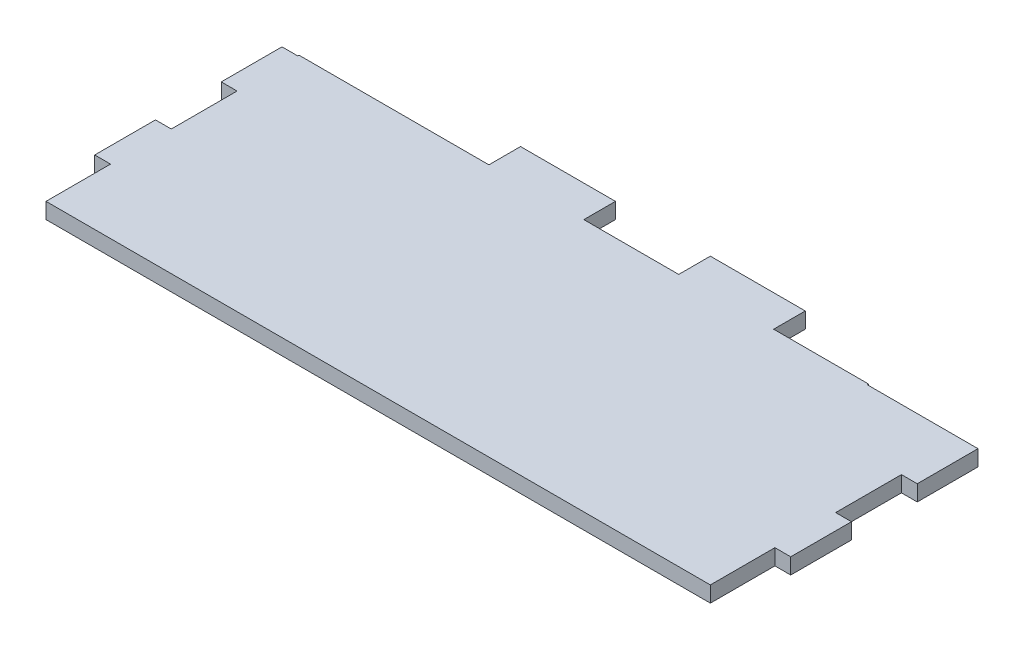
SolidWorks part; units mm, degrees
ref_plane "Front Plane" through (0, 0, 0) normal (0, 0, 1) x (1, 0, 0)
ref_plane "Top Plane" through (0, 0, 0) normal (0, 1, 0) x (1, 0, 0)
ref_plane "Right Plane" through (0, 0, 0) normal (1, 0, 0) x (0, 0, -1)
sketch "Sketch1" plane through (0, 0, 0) normal (0, 1, 0) x (1, 0, 0)
  line L1 (-66.675, -50.8) -> (66.675, -50.8)
  line L2 (-66.675, -50.8) -> (-66.675, 50.8)
  line L3 (-66.675, 50.8) -> (66.675, 50.8)
  line L4 (66.675, -50.8) -> (66.675, 50.8)
  line L5 (-66.675, -50.8) -> (66.675, 50.8) construction
  line L6 (-66.675, 50.8) -> (66.675, -50.8) construction
  point P0 (0, 0)
  dimension "D1" = 133.35
  dimension "D2" = 101.6
extrude "Boss-Extrude1" add sketch "Sketch1" along normal blind 3.175
sketch "Sketch2" plane through (0, 0, 0) normal (0, -1, 0) x (-1, 0, 0)
  line L0 (66.675, 50.8) -> (66.675, -50.8) construction
  line L1 (66.675, -37.846) -> (69.85, -37.846)
  line L2 (66.675, -37.846) -> (66.675, -25.654)
  line L3 (66.675, -25.654) -> (69.85, -25.654)
  line L4 (69.85, -37.846) -> (69.85, -25.654)
  line L6 (66.675, -12.446) -> (69.85, -12.446)
  line L7 (66.675, -12.446) -> (66.675, -0.254)
  line L8 (66.675, -0.254) -> (69.85, -0.254)
  line L9 (69.85, -12.446) -> (69.85, -0.254)
  line L10 (66.675, 12.954) -> (69.85, 12.954)
  line L11 (66.675, 12.954) -> (66.675, 25.146)
  line L12 (66.675, 25.146) -> (69.85, 25.146)
  line L13 (69.85, 12.954) -> (69.85, 25.146)
  line L14 (66.675, 38.354) -> (69.85, 38.354)
  line L15 (66.675, 38.354) -> (66.675, 50.546)
  line L16 (66.675, 50.546) -> (69.85, 50.546)
  line L17 (69.85, 38.354) -> (69.85, 50.546)
  line L18 (0, 0) -> (0, -50.8) construction
  line L19 (66.675, -50.8) -> (-66.675, -50.8) construction
  line L20 (-69.85, 38.354) -> (-69.85, 50.546)
  line L21 (-66.675, 50.546) -> (-69.85, 50.546)
  line L22 (-66.675, 38.354) -> (-66.675, 50.546)
  line L23 (-66.675, 38.354) -> (-69.85, 38.354)
  line L24 (-69.85, 12.954) -> (-69.85, 25.146)
  line L25 (-66.675, 25.146) -> (-69.85, 25.146)
  line L26 (-66.675, 12.954) -> (-66.675, 25.146)
  line L27 (-66.675, 12.954) -> (-69.85, 12.954)
  line L28 (-69.85, -12.446) -> (-69.85, -0.254)
  line L29 (-66.675, -0.254) -> (-69.85, -0.254)
  line L30 (-66.675, -12.446) -> (-66.675, -0.254)
  line L31 (-66.675, -12.446) -> (-69.85, -12.446)
  line L32 (-69.85, -37.846) -> (-69.85, -25.654)
  line L33 (-66.675, -25.654) -> (-69.85, -25.654)
  line L34 (-66.675, -37.846) -> (-66.675, -25.654)
  line L35 (-66.675, -37.846) -> (-69.85, -37.846)
  line L36 (28.575, 57.15) -> (9.525, 57.15)
  line L37 (66.675, 50.8) -> (47.625, 50.8)
  line L38 (66.675, 50.8) -> (66.675, 57.15)
  line L39 (66.675, 57.15) -> (47.625, 57.15)
  line L40 (47.625, 50.8) -> (47.625, 57.15)
  line L41 (9.525, 50.8) -> (9.525, 57.15)
  line L42 (28.575, 50.8) -> (9.525, 50.8)
  line L43 (28.575, 50.8) -> (28.575, 57.15)
  line L44 (-9.525, 57.15) -> (-28.575, 57.15)
  line L45 (-28.575, 50.8) -> (-28.575, 57.15)
  line L46 (-9.525, 50.8) -> (-28.575, 50.8)
  line L47 (-9.525, 50.8) -> (-9.525, 57.15)
  line L48 (-47.625, 57.15) -> (-66.675, 57.15)
  line L49 (-66.675, 50.8) -> (-66.675, 57.15)
  line L50 (-47.625, 50.8) -> (-66.675, 50.8)
  line L51 (-47.625, 50.8) -> (-47.625, 57.15)
  point P6 (69.85, -31.75)
  point P46 (66.675, 53.975)
  dimension "D1" = 3.175
  dimension "D2" = 19.05
  dimension "D3" = 12.192
  dimension "D5" = 6.35
  dimension "D6" = 19.05
  dimension "D8" = 38.1
  dimension "D4" = 4
  dimension "D7" = 4
extrude "Boss-Extrude2" add sketch "Sketch2" against normal blind 3.175
sketch "Sketch3" plane through (0, 0, 0) normal (0, 1, 0) x (1, 0, 0)
  line L1 (-66.675, 57.15) -> (-47.625, 57.15)
  line L2 (-66.675, 57.15) -> (-66.675, 50.8)
  line L3 (-66.675, 50.8) -> (-47.625, 50.8)
  line L4 (-47.625, 57.15) -> (-47.625, 50.8)
  line L5 (47.625, 57.15) -> (66.675, 57.15)
  line L6 (47.625, 57.15) -> (47.625, 50.546)
  line L7 (47.625, 50.546) -> (66.675, 50.546)
  line L8 (66.675, 57.15) -> (66.675, 50.546)
extrude "Cut-Extrude1" cut sketch "Sketch3" along normal through all
sketch "Sketch4" plane through (0, 0, 0) normal (0, 1, 0) x (1, 0, 0)
  line L0 (-28.575, 50.8) -> (-66.675, 50.8) construction
  line L1 (-97.1097, 0) -> (105.1543, 0)
  line L2 (-97.1097, 0) -> (-97.1097, -60.4494)
  line L3 (-97.1097, -60.4494) -> (105.1543, -60.4494)
  line L4 (105.1543, 0) -> (105.1543, -60.4494)
  dimension "D1" = 50.8
extrude "Cut-Extrude2" cut sketch "Sketch4" along normal through all
